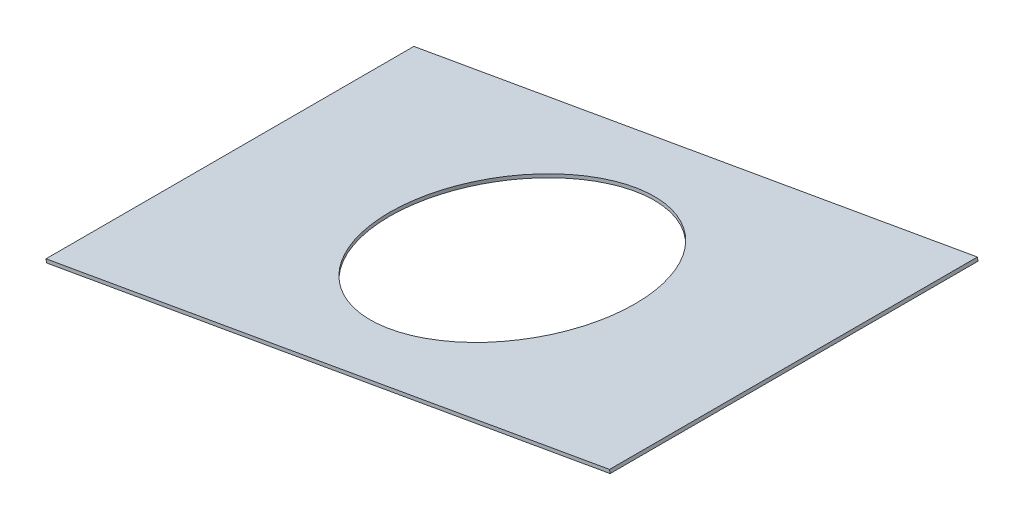
SolidWorks part; units mm, degrees
ref_plane "Front Plane" through (0, 0, 0) normal (0, 0, 1) x (1, 0, 0)
ref_plane "Top Plane" through (0, 0, 0) normal (0, 1, 0) x (1, 0, 0)
ref_plane "Right Plane" through (0, 0, 0) normal (1, 0, 0) x (0, 0, -1)
sketch "Sketch1" plane through (0, 0, 0) normal (0, 0, 1) x (1, 0, 0)
  line L0 (-414.4875, -33.0082) -> (412.751, 112.8563)
  line L1 (-414.4875, -33.0082) -> (-413.6193, -37.9322)
  line L2 (412.751, 112.8563) -> (413.6193, 107.9322)
  line L3 (-413.6193, -37.9322) -> (413.6193, 107.9322)
  line L4 (-326.951, 0) -> (326.951, 0) construction
  point P0 (0, 35)
  point P8 (0, 0)
  dimension "D1" = 10
  dimension "D2" = 5
  dimension "D3" = 840
  dimension "D4" = 35
extrude "Boss-Extrude1" add sketch "Sketch1" along normal mid plane 540
sketch "Sketch2" plane through (0, 0, 0) normal (0, 1, 0) x (1, 0, 0)
  circle A0 centre (0, 0) radius 180
  dimension "D1" = 360
extrude "Cut-Extrude1" cut sketch "Sketch2" along normal up to surface (40.0771 mm away)
